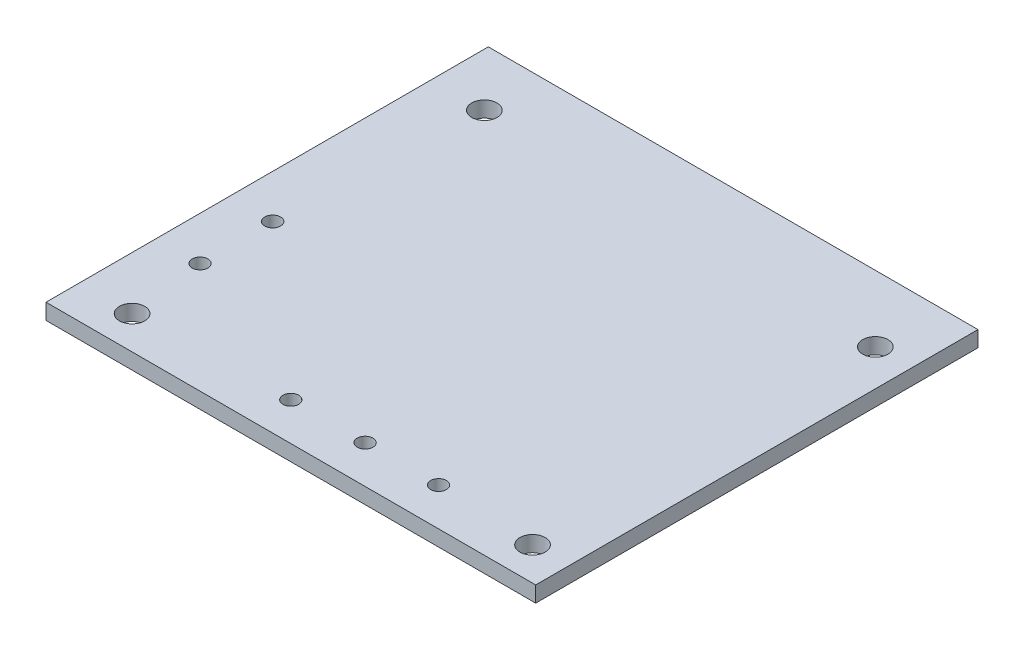
SolidWorks part; units mm, degrees
material "PBT Общее назначение"
ref_plane "Спереди" through (0, 0, 0) normal (0, 0, 1) x (1, 0, 0)
ref_plane "Сверху" through (0, 0, 0) normal (0, 1, 0) x (1, 0, 0)
ref_plane "Справа" through (0, 0, 0) normal (1, 0, 0) x (0, 0, -1)
other "Configuration Table"
sketch "Эскиз1" plane through (0, 0, 0) normal (0, 1, 0) x (1, 0, 0)
  line L1 (0, 0) -> (62, 0)
  line L2 (0, 0) -> (0, -56)
  line L3 (0, -56) -> (62, -56)
  line L4 (62, 0) -> (62, -56)
  dimension "D1" = 62
  dimension "D2" = 56
extrude "Бобышка-Вытянуть1" add sketch "Эскиз1" along normal blind 2
sketch "Эскиз2" plane through (0, 2, 0) normal (0, 1, 0) x (1, 0, 0)
  line L0 (62, 0) -> (0, 0) construction
  line L1 (0, 0) -> (0, -56) construction
  circle A0 centre (6.7, -7.2) radius 1.6
  circle A1 centre (6.7, -51.8) radius 1.6
  circle A2 centre (57.4, -51.8) radius 1.6
  circle A3 centre (57.4, -8.4) radius 1.6
  dimension "D1" = 3.2
  dimension "D2" = 7.2
  dimension "D3" = 6.7
  dimension "D4" = 57.4
  dimension "D5" = 8.4
  dimension "D6" = 6.7
  dimension "D7" = 44.6
  dimension "D8" = 51.8
  dimension "D9" = 57.4
  dimension "D10" = 50.7
  dimension "D11" = 43.4
extrude "Вырез-Вытянуть1" cut sketch "Эскиз2" against normal blind 2
sketch "Эскиз3" plane through (0, 2, 0) normal (0, 1, 0) x (1, 0, 0)
  line L0 (0, 0) -> (0, -56) construction
  line L1 (62, 0) -> (0, 0) construction
  circle A0 centre (5.5, -32.8) radius 1
  circle A1 centre (5.5, -42) radius 1
  circle A2 centre (26.2, -51.2) radius 1
  circle A3 centre (35.6, -51.2) radius 1
  circle A4 centre (44.9, -51.2) radius 1
  dimension "D1" = 2
  dimension "D2" = 2
  dimension "D6" = 2
  dimension "D3" = 5.5
  dimension "D4" = 32.8
  dimension "D5" = 42
  dimension "D7" = 51.2
  dimension "D8" = 26.2
  dimension "D9" = 35.6
  dimension "D10" = 44.9
extrude "Вырез-Вытянуть2" cut sketch "Эскиз3" against normal through all
